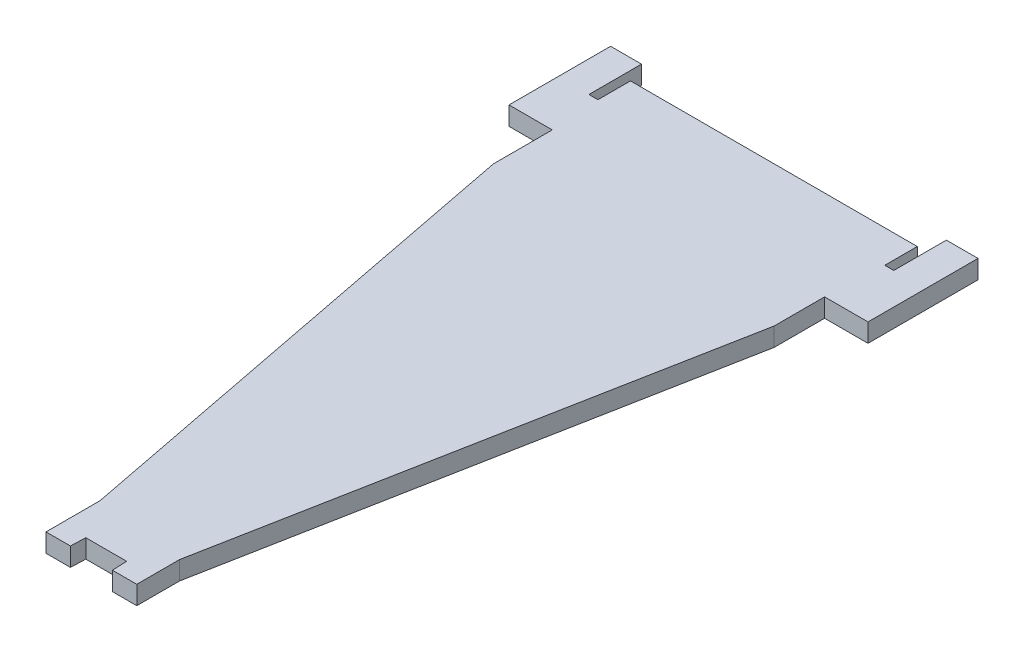
SolidWorks part; units mm, degrees
material "Actuator"
ref_plane "Front Plane" through (0, 0, 0) normal (0, 0, 1) x (1, 0, 0)
ref_plane "Top Plane" through (0, 0, 0) normal (0, 1, 0) x (1, 0, 0)
ref_plane "Right Plane" through (0, 0, 0) normal (1, 0, 0) x (0, 0, -1)
sketch "Sketch1" plane through (0, 0, 0) normal (0, 1, 0) x (1, 0, 0)
  line L0 (65.7711, 123.5882) -> (67.5611, 132.9985)
  line L1 (62.2711, 132.9985) -> (64.0611, 123.7985)
  line L2 (67.5611, 133.9499) -> (67.5611, 132.9985)
  line L3 (61.4562, 136.0226) -> (61.4562, 134.1085)
  line L4 (61.4562, 136.0226) -> (62.0386, 136.0226)
  line L5 (62.0386, 136.0226) -> (62.0386, 135.0319)
  line L6 (62.0386, 135.0319) -> (62.2086, 135.0319)
  line L7 (62.2086, 135.0319) -> (62.2086, 135.6447)
  line L8 (62.2086, 135.6447) -> (67.6124, 135.6447)
  line L9 (67.6124, 135.6447) -> (67.6124, 135.0319)
  line L10 (67.6124, 135.0319) -> (67.7824, 135.0319)
  line L11 (67.7824, 135.0319) -> (67.7824, 136.0226)
  line L12 (67.7824, 136.0226) -> (68.3786, 136.0226)
  line L13 (68.3786, 136.0226) -> (68.3786, 133.9499)
  line L14 (67.5611, 133.9499) -> (68.3786, 133.9499)
  line L15 (64.0611, 123.7985) -> (64.0611, 122.7801)
  line L16 (64.0611, 122.7801) -> (64.5211, 122.7801)
  line L17 (64.5211, 122.7801) -> (64.5311, 123.0601)
  line L18 (64.5311, 123.0601) -> (65.3011, 123.0601)
  line L19 (65.3011, 123.0601) -> (65.3111, 122.7801)
  line L20 (65.3111, 122.7801) -> (65.7711, 122.7801)
  line L21 (65.7711, 122.7801) -> (65.7711, 123.5882)
  line L22 (62.2711, 132.9985) -> (62.2711, 134.1085)
  line L23 (61.4562, 134.1085) -> (62.2711, 134.1085)
  dimension "D1" = 5.29
  dimension "D2" = 9.2
  dimension "D3" = 1.0184
  dimension "D4" = 1.11
  dimension "D5" = 0.8149
  dimension "D6" = 1.9141
  dimension "D7" = 0.9906
extrude "Boss-Extrude1" add sketch "Sketch1" along normal blind 0.35
